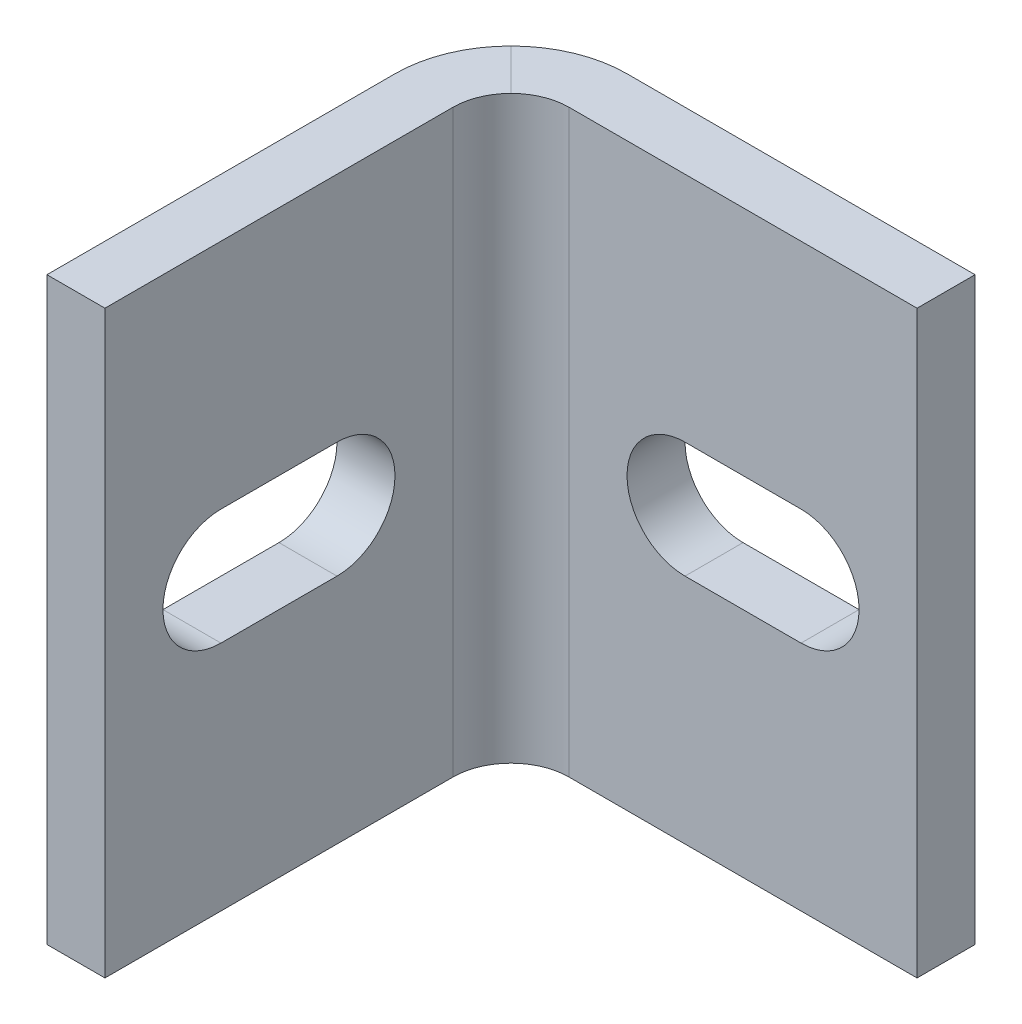
SolidWorks part; units mm, degrees
ref_plane "Front Plane" through (0, 0, 0) normal (0, 0, 1) x (1, 0, 0)
ref_plane "Top Plane" through (0, 0, 0) normal (0, 1, 0) x (1, 0, 0)
ref_plane "Right Plane" through (0, 0, 0) normal (1, 0, 0) x (0, 0, -1)
sketch "Sketch1" plane through (0, 0, 0) normal (0, 0, 1) x (1, 0, 0)
  line L0 (0, 15.875) -> (0, -15.875)
  line L1 (0, 0) -> (3.175, 0)
  point P4 (0, 0)
  point P8 (0, 0)
  point P9 (0, 0)
sketch "Sketch2" plane through (0, 0, 0) normal (0, 1, 0) x (1, 0, 0)
  line L0 (0, 0) -> (0, 22.225)
  line L1 (3.175, 25.4) -> (25.4, 25.4)
  arc A0 (3.175, 25.4) -> (0, 22.225) centre (3.175, 22.225) ccw
  point P6 (0, 25.4)
sketch "Sketch3" plane through (0, 0, 0) normal (0, 0, 1) x (1, 0, 0)
  line L8 (3.175, -15.875) -> (0, -15.875)
  line L9 (3.175, -15.875) -> (3.175, 15.875)
  line L10 (0, -15.875) -> (0, 15.875)
  line L11 (3.175, 15.875) -> (0, 15.875)
  line L12 (3.175, -15.875) -> (0, 15.875) construction
  line L13 (0, -15.875) -> (3.175, 15.875) construction
  line L14 (0, 0) -> (3.175, 0) construction
  point P1 (0, 0)
  point P2 (1.5875, 0)
  dimension "D1" = 3.175
  dimension "D2" = 31.75
  dimension "D3" = 15.875
sketch "Sketch4" plane through (0, 0, 0) normal (0, 1, 0) x (1, 0, 0)
  line L0 (0, 0) -> (0, 25.4)
  line L1 (0, 25.4) -> (25.4, 25.4)
  dimension "D1" = 25.4
  dimension "D2" = 25.4
sweep "Sweep1" add profiles "Sketch3" path "Sketch4"
fillet "Fillet1" radius 3.175 1 edges at (3.175, 0, -22.225)
fillet "Fillet2" radius 6.35 1 edges at (0, 0, -25.4)
sketch "Sketch5" plane through (0, 0, 0) normal (1, 0, 0) x (0, 0, -1)
  line L0 (0, 0) -> (19.05, 0) construction
  line L1 (19.05, -15.875) -> (19.05, 15.875) construction
  line L2 (9.525, 3.175) -> (9.525, -3.175)
  point P8 (9.525, 0)
sketch "Sketch6" plane through (0, 0, 0) normal (1, 0, 0) x (0, 0, -1)
  line L0 (0, 0) -> (19.05, 0) construction
  line L1 (19.05, -15.875) -> (19.05, 15.875) construction
  line L2 (12.7, 0) -> (6.35, 0) construction
  line L3 (12.7, -3.175) -> (6.35, -3.175)
  line L4 (12.7, 3.175) -> (6.35, 3.175)
  arc A0 (12.7, -3.175) -> (12.7, 3.175) centre (12.7, 0) ccw
  arc A1 (6.35, 3.175) -> (6.35, -3.175) centre (6.35, 0) ccw
  point P7 (9.525, 0)
  point P12 (3.175, 0)
  dimension "D1" = 3.175
  dimension "D2" = 6.35
extrude "Cut-Extrude2" cut sketch "Sketch6" along normal up to next
sketch "Sketch7" plane through (0, 0, -22.225) normal (0, 0, 1) x (1, 0, 0)
  line L0 (25.4, 0) -> (6.35, 0) construction
  line L1 (25.4, -15.875) -> (25.4, 15.875) construction
  line L2 (6.35, 15.875) -> (6.35, -15.875) construction
  line L3 (12.7, 0) -> (19.05, 0) construction
  line L4 (12.7, 3.175) -> (19.05, 3.175)
  line L5 (12.7, -3.175) -> (19.05, -3.175)
  arc A0 (12.7, 3.175) -> (12.7, -3.175) centre (12.7, 0) ccw
  arc A1 (19.05, -3.175) -> (19.05, 3.175) centre (19.05, 0) ccw
  point P8 (15.875, 0)
  point P13 (22.225, 0)
  dimension "D1" = 3.175
  dimension "D2" = 6.35
extrude "Cut-Extrude3" cut sketch "Sketch7" against normal through all
equation "\"D1@Sketch3\"=\"Thickness@Sketch1\""
equation "\"D2@Sketch3\"=\"LengthC@Sketch1\""
equation "\"D3@Sketch3\"=\"LengthC@Sketch1\"/2"
equation "\"D1@Sketch4\"=\"LengthA@Sketch2\""
equation "\"D2@Sketch4\"=\"LengthB@Sketch2\""
equation "\"D1@Fillet1\"=\"CornerRadius@Sketch2\""
equation "\"D1@Fillet2\"=\"CornerRadius@Sketch2\"*2"
equation "\"D2@Sketch6\"=\"ScrewSize@Sketch5\""
equation "\"D2@Sketch7\"=\"ScrewSize@Sketch5\""
